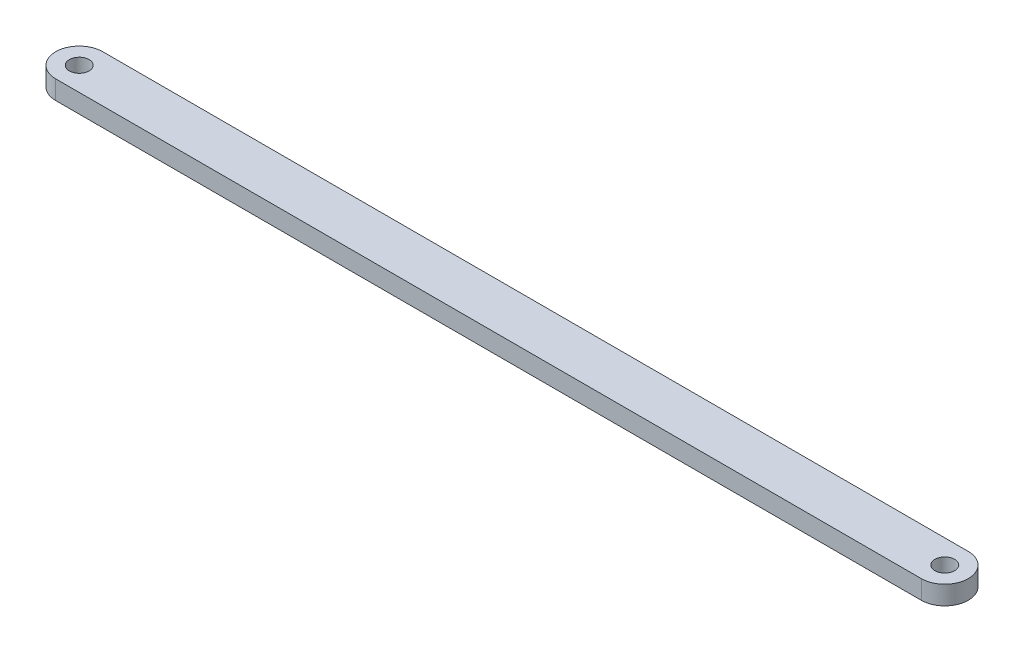
SolidWorks part; units mm, degrees
ref_plane "Front Plane" through (0, 0, 0) normal (0, 0, 1) x (1, 0, 0)
ref_plane "Top Plane" through (0, 0, 0) normal (0, 1, 0) x (1, 0, 0)
ref_plane "Right Plane" through (0, 0, 0) normal (1, 0, 0) x (0, 0, -1)
sketch "Sketch1" plane through (0, 0, 0) normal (0, 1, 0) x (1, 0, 0)
  line L0 (0, 0) -> (92, 0) construction
  line L1 (0, 2.5) -> (92, 2.5)
  line L2 (0, -2.5) -> (92, -2.5)
  arc A0 (0, 2.5) -> (0, -2.5) centre (0, 0) ccw
  arc A1 (92, -2.5) -> (92, 2.5) centre (92, 0) ccw
  circle A2 centre (0, 0) radius 1.05
  circle A3 centre (92, 0) radius 1.05
  point P3 (46, 0)
  dimension "D1" = 2.5
  dimension "D3" = 2.1
  dimension "D4" = 2.1
  dimension "D2" = 92
extrude "Boss-Extrude1" add sketch "Sketch1" along normal blind 2
